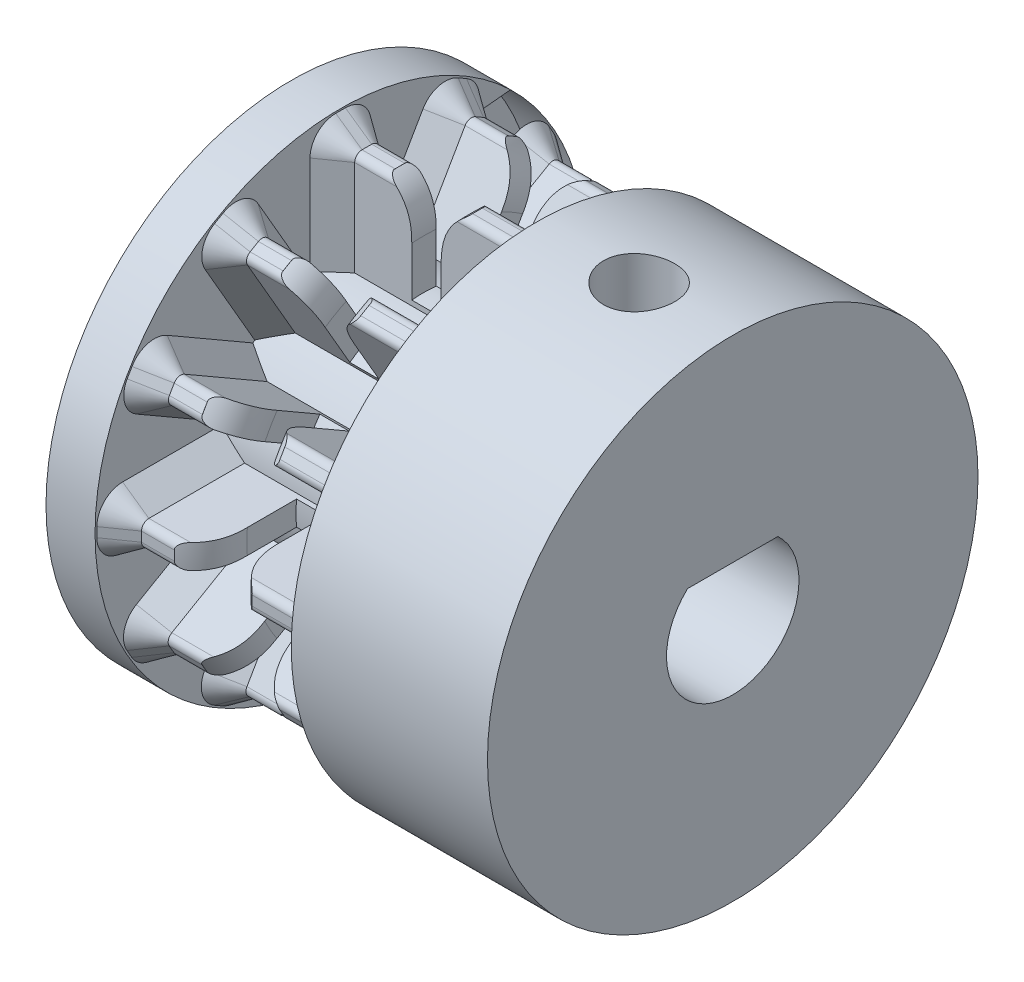
SolidWorks part; units mm, degrees
ref_plane "Спереди" through (0, 0, 0) normal (0, 0, 1) x (1, 0, 0)
ref_plane "Сверху" through (0, 0, 0) normal (0, 1, 0) x (1, 0, 0)
ref_plane "Справа" through (0, 0, 0) normal (1, 0, 0) x (0, 0, -1)
sketch "Эскиз1" plane through (0, 0, 0) normal (1, 0, 0) x (0, 0, -1)
  circle A1 centre (0, 0) radius 10
extrude "Бобышка-Вытянуть1" add sketch "Эскиз1" along normal blind 2
sketch "Эскиз2" plane through (2, 0, 0) normal (1, 0, 0) x (0, 0, -1)
  line L0 (0, 0) -> (0, 5)
  line L1 (4.018, 7.9295) -> (2.0676, 4.5513)
  line L2 (2.9264, 4.0542) -> (4.8774, 7.4334)
  line L3 (4.7676, 7.8432) -> (4.4278, 8.0393)
  line L4 (7.4445, 4.8581) -> (4.0663, 2.9077)
  line L5 (4.5614, 2.0478) -> (7.9406, 3.9988)
  line L6 (8.0504, 4.4086) -> (7.8543, 4.7483)
  line L7 (8.8762, 0.485) -> (4.9753, 0.485)
  line L8 (4.9742, -0.5072) -> (8.8762, -0.5072)
  line L9 (9.1762, -0.2072) -> (9.1762, 0.185)
  line L10 (7.9295, -4.018) -> (4.5513, -2.0676)
  line L11 (4.0542, -2.9264) -> (7.4334, -4.8774)
  line L12 (7.8432, -4.7676) -> (8.0393, -4.4278)
  line L13 (4.8581, -7.4445) -> (2.9077, -4.0663)
  line L14 (2.0478, -4.5614) -> (3.9988, -7.9406)
  line L15 (4.4086, -8.0504) -> (4.7483, -7.8543)
  line L16 (0.485, -8.8762) -> (0.485, -4.9753)
  line L17 (-0.5072, -4.9742) -> (-0.5072, -8.8762)
  line L18 (-0.2072, -9.1762) -> (0.185, -9.1762)
  line L19 (-4.018, -7.9295) -> (-2.0676, -4.5513)
  line L20 (-2.9264, -4.0542) -> (-4.8774, -7.4334)
  line L21 (-4.7676, -7.8432) -> (-4.4278, -8.0393)
  line L22 (-7.4445, -4.8581) -> (-4.0663, -2.9077)
  line L23 (-4.5614, -2.0478) -> (-7.9406, -3.9988)
  line L24 (-8.0504, -4.4086) -> (-7.8543, -4.7483)
  line L25 (-8.8762, -0.485) -> (-4.9753, -0.485)
  line L26 (-4.9742, 0.5072) -> (-8.8762, 0.5072)
  line L27 (-9.1762, 0.2072) -> (-9.1762, -0.185)
  line L28 (-7.9295, 4.018) -> (-4.5513, 2.0676)
  line L29 (-4.0542, 2.9264) -> (-7.4334, 4.8774)
  line L30 (-7.8432, 4.7676) -> (-8.0393, 4.4278)
  line L31 (-4.8581, 7.4445) -> (-2.9077, 4.0663)
  line L32 (-2.0478, 4.5614) -> (-3.9988, 7.9406)
  line L33 (-4.4086, 8.0504) -> (-4.7483, 7.8543)
  line L58 (0, 5) -> (0, 8.8762)
  line L60 (-0.485, 8.8762) -> (-0.485, 4.9753)
  line L61 (-0.485, 4.9753) -> (0.5072, 4.9742)
  line L62 (0.5072, 4.9742) -> (0.5072, 8.8762)
  line L63 (0.2072, 9.1762) -> (-0.185, 9.1762)
  circle A0 centre (0, 0) radius 5
  circle A1 centre (0, 0) radius 4.9989
  arc A2 (0.2072, 9.1762) -> (0.5072, 8.8762) centre (0.2072, 8.8762) cw
  arc A3 (-0.185, 9.1762) -> (-0.485, 8.8762) centre (-0.185, 8.8762) ccw
  arc A4 (4.4278, 8.0393) -> (4.018, 7.9295) centre (4.2778, 7.7795) ccw
  arc A5 (4.7676, 7.8432) -> (4.8774, 7.4334) centre (4.6176, 7.5834) cw
  arc A6 (7.8543, 4.7483) -> (7.4445, 4.8581) centre (7.5945, 4.5983) ccw
  arc A7 (8.0504, 4.4086) -> (7.9406, 3.9988) centre (7.7906, 4.2586) cw
  arc A8 (9.1762, 0.185) -> (8.8762, 0.485) centre (8.8762, 0.185) ccw
  arc A9 (9.1762, -0.2072) -> (8.8762, -0.5072) centre (8.8762, -0.2072) cw
  arc A10 (8.0393, -4.4278) -> (7.9295, -4.018) centre (7.7795, -4.2778) ccw
  arc A11 (7.8432, -4.7676) -> (7.4334, -4.8774) centre (7.5834, -4.6176) cw
  arc A12 (4.7483, -7.8543) -> (4.8581, -7.4445) centre (4.5983, -7.5945) ccw
  arc A13 (4.4086, -8.0504) -> (3.9988, -7.9406) centre (4.2586, -7.7906) cw
  arc A14 (0.185, -9.1762) -> (0.485, -8.8762) centre (0.185, -8.8762) ccw
  arc A15 (-0.2072, -9.1762) -> (-0.5072, -8.8762) centre (-0.2072, -8.8762) cw
  arc A16 (-4.4278, -8.0393) -> (-4.018, -7.9295) centre (-4.2778, -7.7795) ccw
  arc A17 (-4.7676, -7.8432) -> (-4.8774, -7.4334) centre (-4.6176, -7.5834) cw
  arc A18 (-7.8543, -4.7483) -> (-7.4445, -4.8581) centre (-7.5945, -4.5983) ccw
  arc A19 (-8.0504, -4.4086) -> (-7.9406, -3.9988) centre (-7.7906, -4.2586) cw
  arc A20 (-9.1762, -0.185) -> (-8.8762, -0.485) centre (-8.8762, -0.185) ccw
  arc A21 (-9.1762, 0.2072) -> (-8.8762, 0.5072) centre (-8.8762, 0.2072) cw
  arc A22 (-8.0393, 4.4278) -> (-7.9295, 4.018) centre (-7.7795, 4.2778) ccw
  arc A23 (-7.8432, 4.7676) -> (-7.4334, 4.8774) centre (-7.5834, 4.6176) cw
  arc A24 (-4.7483, 7.8543) -> (-4.8581, 7.4445) centre (-4.5983, 7.5945) ccw
  arc A25 (-4.4086, 8.0504) -> (-3.9988, 7.9406) centre (-4.2586, 7.7906) cw
  point P65 (0, 0)
  point P102 (0, 0)
  dimension "D1" = 0.3
  dimension "D2" = 12
extrude "Бобышка-Вытянуть2" add sketch "Эскиз2" along normal blind 8
sketch "Эскиз3" plane through (10, 0, 0) normal (1, 0, 0) x (0, 0, -1)
  circle A0 centre (0, 0) radius 10
extrude "Бобышка-Вытянуть3" add sketch "Эскиз3" along normal blind 8
sketch "Эскиз4" plane through (18, 0, 0) normal (1, 0, 0) x (0, 0, -1)
  line L1 (-0.0683, 1.9731) -> (1.8431, 1.9731)
  line L2 (1.8431, 1.9731) -> (-1.8431, 1.9731)
  arc A0 (-1.8431, 1.9731) -> (1.8431, 1.9731) centre (0, 0) ccw
extrude "Вырез-Вытянуть1" cut sketch "Эскиз4" against normal through all contours L2 A0 L1
sketch "Эскиз5" plane through (0, 1.9731, 0) normal (0, -1, 0) x (-1, 0, 0)
  circle A0 centre (-14.1831, 0) radius 1.45
extrude "Вырез-Вытянуть2" cut sketch "Эскиз5" against normal blind 9
ref_plane "Плоскость1" through (0, 0, 0) normal (0, 1, 0) x (1, 0, 0)
sketch "Эскиз7" plane through (0, 0, 0) normal (0, 1, 0) x (1, 0, 0)
  line L1 (0, 0) -> (24.0943, 0)
  line L2 (6, -5.2061) -> (5.3985, -5.2061)
  line L3 (5.3985, -5.2061) -> (5.3985, -9.4956)
  line L4 (5.3985, -9.4956) -> (6.5975, -9.4956)
  line L5 (6.5975, -9.4956) -> (6.5975, -5.2061)
  line L6 (6.5975, -5.2061) -> (6, -5.2061)
  line L7 (7.5803, -9.1746) -> (7.5803, -9.4956)
  line L8 (7.5803, -9.4956) -> (4.4157, -9.4956)
  line L9 (4.4157, -9.4956) -> (4.4157, -9.1746)
  spline S0 degree 2 poles (6.5975, -7.2071) (6.6169, -8.4834) (7.5803, -9.1746) knots 0 0 0 1 1 1
  spline S1 degree 2 poles (5.3985, -7.2071) (5.4358, -8.5228) (4.4157, -9.1746) knots 0 0 0 1 1 1
revolve "Вырез-Повернуть5" cut sketch "Эскиз7" angle 360 about L1
chamfer "Фаска1" distance 0.75 angle 55 60 edges at (2, 3.0431, 6.2409) (2, 4.2002, 8.0693) (2, 4.5977, 7.9412) (2, 4.9073, 7.661) (2, 3.9019, 5.7438) (2, -6.2409, 3.0431) (2, -8.0693, 4.2002) (2, -7.9412, 4.5977) (2, -7.661, 4.9073) (2, -5.7438, 3.9019) (2, -6.9263, -0.485) (2, -9.0883, -0.3972) (2, -9.1762, 0.0111) (2, -9.0883, 0.4194) (2, -6.9252, 0.5072) (2, -6.251, -3.0233) (2, -8.0804, -4.181) (2, -7.9523, -4.5785) (2, -7.6721, -4.8881) (2, -5.7558, -3.8832) (2, -3.0431, -6.2409) (2, -4.2002, -8.0693) (2, -4.5977, -7.9412) (2, -4.9073, -7.661) (2, -3.9019, -5.7438) (2, -0.5072, -6.9252) (2, -0.4194, -9.0883) (2, -0.0111, -9.1762) (2, 0.3972, -9.0883) (2, 0.485, -6.9263) (2, 3.0233, -6.251) (2, 4.181, -8.0804) (2, 4.5785, -7.9523) (2, 4.8881, -7.6721) (2, 3.8832, -5.7558) (2, 5.7438, -3.9019) (2, 7.661, -4.9073) (2, 7.9412, -4.5977) (2, 8.0693, -4.2002) (2, 6.2409, -3.0431) (2, 6.9252, -0.5072) (2, 9.0883, -0.4194) (2, 9.1762, -0.0111) (2, 9.0883, 0.3972) (2, 6.9263, 0.485) (2, -3.8832, 5.7558) (2, -4.8881, 7.6721) (2, -4.5785, 7.9523) (2, -4.181, 8.0804) (2, -3.0233, 6.251) (2, -0.485, 6.9263) (2, -0.3972, 9.0883) (2, 0.0111, 9.1762) (2, 0.4194, 9.0883) (2, 0.5072, 6.9252) (2, 6.251, 3.0233) (2, 8.0804, 4.181) (2, 7.9523, 4.5785) (2, 7.6721, 4.8881) (2, 5.7558, 3.8832)
